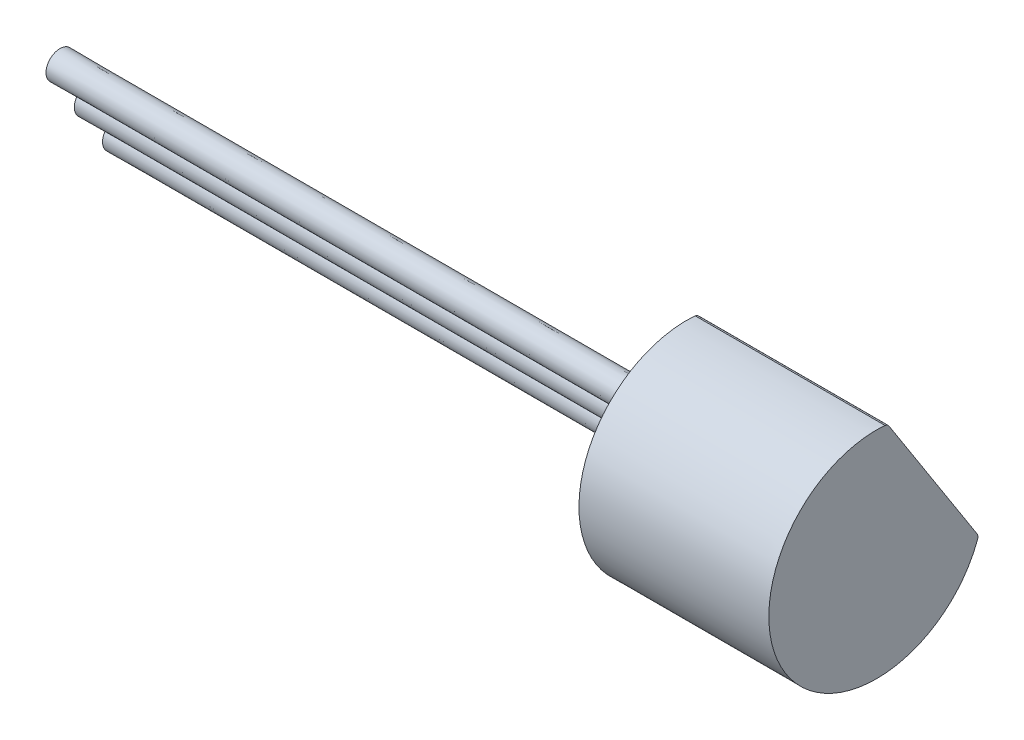
SolidWorks part; units mm, degrees
ref_plane "Front Plane" through (0, 0, 0) normal (1, 0, 0) x (0, 1, 0)
ref_plane "Top Plane" through (0, 0, 0) normal (0, 0, 1) x (0, 1, 0)
ref_plane "Right Plane" through (0, 0, 0) normal (0, 1, 0) x (-1, 0, 0)
sketch "Sketch1" plane through (0, 0, 0) normal (1, 0, 0) x (0, 1, 0)
  line L0 (229.6743, -151.1433) -> (226.3261, -153.2901) construction
  line L1 (229.6743, -151.1433) -> (226.3261, -153.2901)
  line L2 (226.3261, -153.2901) -> (226.2725, -153.3079) construction
  line L3 (226.2725, -153.3079) -> (226.2164, -153.3006) construction
  line L4 (229.7235, -151.0547) -> (229.7067, -151.1087) construction
  line L5 (229.7067, -151.1087) -> (229.6743, -151.1433) construction
  line L6 (226.3261, -153.2901) -> (226.2725, -153.3079)
  line L7 (226.2725, -153.3079) -> (226.2164, -153.3006)
  line L8 (229.7235, -151.0547) -> (229.7067, -151.1087)
  line L9 (229.7067, -151.1087) -> (229.6743, -151.1433)
  spline S0 degree 3 poles (227.8479, -150.2251) (227.8972, -150.3509) (227.9908, -150.4482) (228.1146, -150.5024) (228.2496, -150.505) (228.3754, -150.4557) (228.4727, -150.3621) (228.5268, -150.2383) (228.5295, -150.1033) (228.4802, -149.9775) (228.3866, -149.8802) (228.2628, -149.8261) (228.1278, -149.8234) (228.002, -149.8727) (227.9046, -149.9663) (227.8505, -150.0901) (227.8479, -150.2251) (227.8972, -150.3509) (227.9908, -150.4482) knots -0.1875 -0.125 -0.0625 0 0.0625 0.125 0.1875 0.25 0.3125 0.375 0.4375 0.5 0.5625 0.625 0.6875 0.75 0.8125 0.875 0.9375 1 1.0625 1.125 1.1875 only from (227.9046, -150.3462) to (227.9046, -150.3462) construction
  spline S1 degree 3 poles (226.7784, -150.91) (226.8277, -151.0358) (226.9213, -151.1331) (227.0451, -151.1872) (227.1801, -151.1899) (227.3059, -151.1406) (227.4032, -151.047) (227.4573, -150.9232) (227.46, -150.7882) (227.4107, -150.6624) (227.3171, -150.5651) (227.1933, -150.511) (227.0583, -150.5083) (226.9325, -150.5576) (226.8352, -150.6512) (226.781, -150.775) (226.7784, -150.91) (226.8277, -151.0358) (226.9213, -151.1331) knots -0.1875 -0.125 -0.0625 0 0.0625 0.125 0.1875 0.25 0.3125 0.375 0.4375 0.5 0.5625 0.625 0.6875 0.75 0.8125 0.875 0.9375 1 1.0625 1.125 1.1875 only from (226.8351, -151.0311) to (226.8351, -151.0311) construction
  spline S2 degree 3 poles (225.7089, -151.5949) (225.7582, -151.7207) (225.8518, -151.818) (225.9756, -151.8721) (226.1106, -151.8748) (226.2364, -151.8255) (226.3337, -151.7319) (226.3878, -151.6081) (226.3905, -151.4731) (226.3412, -151.3473) (226.2476, -151.25) (226.1238, -151.1959) (225.9888, -151.1932) (225.863, -151.2425) (225.7657, -151.3361) (225.7116, -151.4599) (225.7089, -151.5949) (225.7582, -151.7207) (225.8518, -151.818) knots -0.1875 -0.125 -0.0625 0 0.0625 0.125 0.1875 0.25 0.3125 0.375 0.4375 0.5 0.5625 0.625 0.6875 0.75 0.8125 0.875 0.9375 1 1.0625 1.125 1.1875 only from (225.7656, -151.7159) to (225.7656, -151.7159) construction
  spline S3 degree 2 poles (755.9525, 694.8612) (255.0504, -174.4776) (225.5804, -152.9595) (225.2866, -152.745) (225.0621, -152.4574) (224.8382, -152.1706) (224.701, -151.8325) (224.5642, -151.4954) (224.5248, -151.1326) (224.4855, -150.771) (224.5469, -150.4113) (224.6082, -150.0527) (224.7657, -149.7235) (224.9228, -149.3954) (225.1644, -149.122) (225.4053, -148.8493) (225.7125, -148.6525) (226.0188, -148.4562) (226.3682, -148.351) (226.7166, -148.2461) (227.0814, -148.2406) (227.4452, -148.2351) (227.7976, -148.3296) (228.149, -148.4239) (228.462, -148.6113) (228.7742, -148.7981) (229.024, -149.0641) (229.2731, -149.3293) (229.4405, -149.6535) (229.6075, -149.9767) (229.6798, -150.3343) (236.892, -186.0061) (-760.8098, -288.2389) knots -6.192393 -6.192393 -6.192393 0.0625 0.0625 0.125 0.125 0.1875 0.1875 0.25 0.25 0.3125 0.3125 0.375 0.375 0.4375 0.4375 0.5 0.5 0.5625 0.5625 0.625 0.625 0.6875 0.6875 0.75 0.75 0.8125 0.8125 0.875 0.875 0.9375 0.9375 7.185133 7.185133 7.185133 only from (226.2164, -153.3006) to (229.7235, -151.0547) construction
  spline S4 degree 3 poles (227.8479, -150.2251) (227.8972, -150.3509) (227.9908, -150.4482) (228.1146, -150.5024) (228.2496, -150.505) (228.3754, -150.4557) (228.4727, -150.3621) (228.5268, -150.2383) (228.5295, -150.1033) (228.4802, -149.9775) (228.3866, -149.8802) (228.2628, -149.8261) (228.1278, -149.8234) (228.002, -149.8727) (227.9046, -149.9663) (227.8505, -150.0901) (227.8479, -150.2251) (227.8972, -150.3509) (227.9908, -150.4482) knots -0.1875 -0.125 -0.0625 0 0.0625 0.125 0.1875 0.25 0.3125 0.375 0.4375 0.5 0.5625 0.625 0.6875 0.75 0.8125 0.875 0.9375 1 1.0625 1.125 1.1875 only from (227.9046, -150.3462) to (227.9046, -150.3462) construction
  spline S5 degree 3 poles (226.7784, -150.91) (226.8277, -151.0358) (226.9213, -151.1331) (227.0451, -151.1872) (227.1801, -151.1899) (227.3059, -151.1406) (227.4032, -151.047) (227.4573, -150.9232) (227.46, -150.7882) (227.4107, -150.6624) (227.3171, -150.5651) (227.1933, -150.511) (227.0583, -150.5083) (226.9325, -150.5576) (226.8352, -150.6512) (226.781, -150.775) (226.7784, -150.91) (226.8277, -151.0358) (226.9213, -151.1331) knots -0.1875 -0.125 -0.0625 0 0.0625 0.125 0.1875 0.25 0.3125 0.375 0.4375 0.5 0.5625 0.625 0.6875 0.75 0.8125 0.875 0.9375 1 1.0625 1.125 1.1875 only from (226.8351, -151.0311) to (226.8351, -151.0311) construction
  spline S6 degree 3 poles (225.7089, -151.5949) (225.7582, -151.7207) (225.8518, -151.818) (225.9756, -151.8721) (226.1106, -151.8748) (226.2364, -151.8255) (226.3337, -151.7319) (226.3878, -151.6081) (226.3905, -151.4731) (226.3412, -151.3473) (226.2476, -151.25) (226.1238, -151.1959) (225.9888, -151.1932) (225.863, -151.2425) (225.7657, -151.3361) (225.7116, -151.4599) (225.7089, -151.5949) (225.7582, -151.7207) (225.8518, -151.818) knots -0.1875 -0.125 -0.0625 0 0.0625 0.125 0.1875 0.25 0.3125 0.375 0.4375 0.5 0.5625 0.625 0.6875 0.75 0.8125 0.875 0.9375 1 1.0625 1.125 1.1875 only from (225.7656, -151.7159) to (225.7656, -151.7159) construction
  spline S7 degree 2 poles (226.2164, -153.3006) (225.8749, -153.1745) (225.5804, -152.9595) (225.2866, -152.745) (225.0621, -152.4574) (224.8382, -152.1706) (224.701, -151.8325) (224.5642, -151.4954) (224.5248, -151.1326) (224.4855, -150.771) (224.5469, -150.4113) (224.6082, -150.0527) (224.7657, -149.7235) (224.9228, -149.3954) (225.1644, -149.122) (225.4053, -148.8493) (225.7125, -148.6525) (226.0188, -148.4562) (226.3682, -148.351) (226.7166, -148.2461) (227.0814, -148.2406) (227.4452, -148.2351) (227.7976, -148.3296) (228.149, -148.4239) (228.462, -148.6113) (228.7742, -148.7981) (229.024, -149.0641) (229.2731, -149.3293) (229.4405, -149.6535) (229.6075, -149.9767) (229.6798, -150.3343) (229.7519, -150.6912) (229.7235, -151.0547) knots 0 0 0 0.0625 0.0625 0.125 0.125 0.1875 0.1875 0.25 0.25 0.3125 0.3125 0.375 0.375 0.4375 0.4375 0.5 0.5 0.5625 0.5625 0.625 0.625 0.6875 0.6875 0.75 0.75 0.8125 0.8125 0.875 0.875 0.9375 0.9375 1 1 1
extrude "Boss-Extrude1" add sketch "Sketch1" along normal blind 4.6
sketch "Sketch2" plane through (0, 0, 0) normal (-1, 0, 0) x (0, -1, 0)
  spline S0 degree 3 poles (-225.8518, -151.818) (-225.7582, -151.7207) (-225.7089, -151.5949) (-225.7116, -151.4599) (-225.7657, -151.3361) (-225.863, -151.2425) (-225.9888, -151.1932) (-226.1238, -151.1959) (-226.2476, -151.25) (-226.3412, -151.3473) (-226.3905, -151.4731) (-226.3878, -151.6081) (-226.3337, -151.7319) (-226.2364, -151.8255) (-226.1106, -151.8748) (-225.9756, -151.8721) (-225.8518, -151.818) (-225.7582, -151.7207) (-225.7089, -151.5949) knots -0.1875 -0.125 -0.0625 0 0.0625 0.125 0.1875 0.25 0.3125 0.375 0.4375 0.5 0.5625 0.625 0.6875 0.75 0.8125 0.875 0.9375 1 1.0625 1.125 1.1875 only from (-225.7656, -151.7159) to (-225.7656, -151.7159) construction
  spline S1 degree 3 poles (-226.9213, -151.1331) (-226.8277, -151.0358) (-226.7784, -150.91) (-226.781, -150.775) (-226.8352, -150.6512) (-226.9325, -150.5576) (-227.0583, -150.5083) (-227.1933, -150.511) (-227.3171, -150.5651) (-227.4107, -150.6624) (-227.46, -150.7882) (-227.4573, -150.9232) (-227.4032, -151.047) (-227.3059, -151.1406) (-227.1801, -151.1899) (-227.0451, -151.1872) (-226.9213, -151.1331) (-226.8277, -151.0358) (-226.7784, -150.91) knots -0.1875 -0.125 -0.0625 0 0.0625 0.125 0.1875 0.25 0.3125 0.375 0.4375 0.5 0.5625 0.625 0.6875 0.75 0.8125 0.875 0.9375 1 1.0625 1.125 1.1875 only from (-226.8351, -151.0311) to (-226.8351, -151.0311) construction
  spline S2 degree 3 poles (-227.9908, -150.4482) (-227.8972, -150.3509) (-227.8479, -150.2251) (-227.8505, -150.0901) (-227.9046, -149.9663) (-228.002, -149.8727) (-228.1278, -149.8234) (-228.2628, -149.8261) (-228.3866, -149.8802) (-228.4802, -149.9775) (-228.5295, -150.1033) (-228.5268, -150.2383) (-228.4727, -150.3621) (-228.3754, -150.4557) (-228.2496, -150.505) (-228.1146, -150.5024) (-227.9908, -150.4482) (-227.8972, -150.3509) (-227.8479, -150.2251) knots -0.1875 -0.125 -0.0625 0 0.0625 0.125 0.1875 0.25 0.3125 0.375 0.4375 0.5 0.5625 0.625 0.6875 0.75 0.8125 0.875 0.9375 1 1.0625 1.125 1.1875 only from (-227.9046, -150.3462) to (-227.9046, -150.3462) construction
  spline S3 degree 3 poles (-225.8518, -151.818) (-225.7582, -151.7207) (-225.7089, -151.5949) (-225.7116, -151.4599) (-225.7657, -151.3361) (-225.863, -151.2425) (-225.9888, -151.1932) (-226.1238, -151.1959) (-226.2476, -151.25) (-226.3412, -151.3473) (-226.3905, -151.4731) (-226.3878, -151.6081) (-226.3337, -151.7319) (-226.2364, -151.8255) (-226.1106, -151.8748) (-225.9756, -151.8721) (-225.8518, -151.818) (-225.7582, -151.7207) (-225.7089, -151.5949) knots -0.1875 -0.125 -0.0625 0 0.0625 0.125 0.1875 0.25 0.3125 0.375 0.4375 0.5 0.5625 0.625 0.6875 0.75 0.8125 0.875 0.9375 1 1.0625 1.125 1.1875 only from (-225.7656, -151.7159) to (-225.7656, -151.7159)
  spline S4 degree 3 poles (-226.9213, -151.1331) (-226.8277, -151.0358) (-226.7784, -150.91) (-226.781, -150.775) (-226.8352, -150.6512) (-226.9325, -150.5576) (-227.0583, -150.5083) (-227.1933, -150.511) (-227.3171, -150.5651) (-227.4107, -150.6624) (-227.46, -150.7882) (-227.4573, -150.9232) (-227.4032, -151.047) (-227.3059, -151.1406) (-227.1801, -151.1899) (-227.0451, -151.1872) (-226.9213, -151.1331) (-226.8277, -151.0358) (-226.7784, -150.91) knots -0.1875 -0.125 -0.0625 0 0.0625 0.125 0.1875 0.25 0.3125 0.375 0.4375 0.5 0.5625 0.625 0.6875 0.75 0.8125 0.875 0.9375 1 1.0625 1.125 1.1875 only from (-226.8351, -151.0311) to (-226.8351, -151.0311)
  spline S5 degree 3 poles (-227.9908, -150.4482) (-227.8972, -150.3509) (-227.8479, -150.2251) (-227.8505, -150.0901) (-227.9046, -149.9663) (-228.002, -149.8727) (-228.1278, -149.8234) (-228.2628, -149.8261) (-228.3866, -149.8802) (-228.4802, -149.9775) (-228.5295, -150.1033) (-228.5268, -150.2383) (-228.4727, -150.3621) (-228.3754, -150.4557) (-228.2496, -150.505) (-228.1146, -150.5024) (-227.9908, -150.4482) (-227.8972, -150.3509) (-227.8479, -150.2251) knots -0.1875 -0.125 -0.0625 0 0.0625 0.125 0.1875 0.25 0.3125 0.375 0.4375 0.5 0.5625 0.625 0.6875 0.75 0.8125 0.875 0.9375 1 1.0625 1.125 1.1875 only from (-227.9046, -150.3462) to (-227.9046, -150.3462)
extrude "Boss-Extrude2" add sketch "Sketch2" along normal blind 14.5
